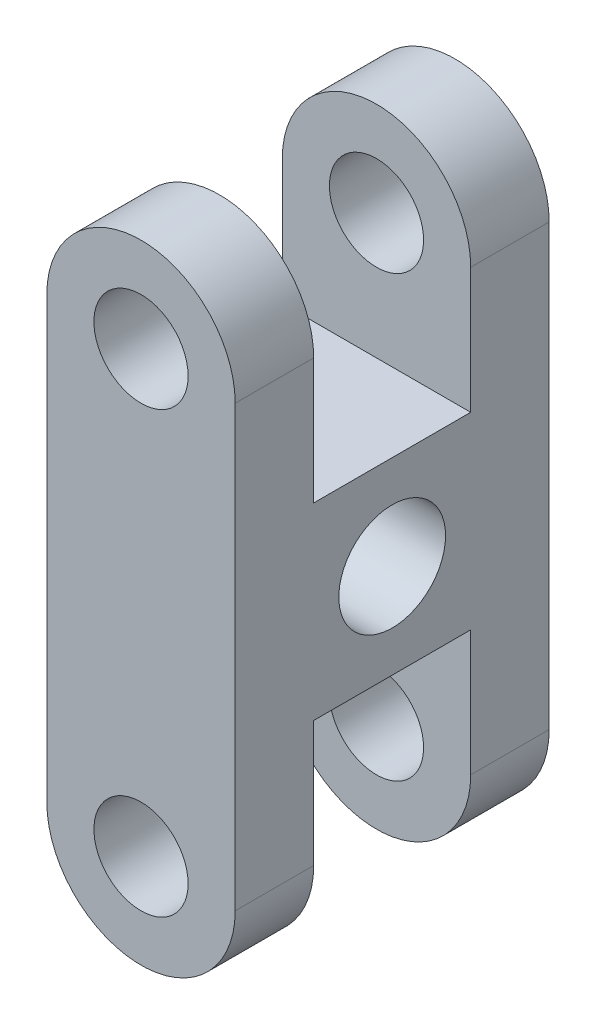
SolidWorks part; units mm, degrees
ref_plane "Plano frontal" through (0, 0, 0) normal (0, 0, 1) x (1, 0, 0)
ref_plane "Plano superior" through (0, 0, 0) normal (0, 1, 0) x (1, 0, 0)
ref_plane "Plano direito" through (0, 0, 0) normal (1, 0, 0) x (0, 0, -1)
sketch "Esboço2" plane through (0, 0, 0) normal (0, 0, 1) x (1, 0, 0)
  line L0 (0, -14) -> (0, 14) construction
  line L1 (-6, -14) -> (-6, 14)
  line L2 (6, -14) -> (6, 14)
  arc A0 (-6, -14) -> (6, -14) centre (0, -14) ccw
  arc A1 (6, 14) -> (-6, 14) centre (0, 14) ccw
  circle A2 centre (0, -14) radius 3
  circle A3 centre (0, 14) radius 3
  point P3 (0, 0)
  dimension "D1" = 6
  dimension "D2" = 6
  dimension "D3" = 28
extrude "Ressalto-extrusão1" add sketch "Esboço2" along normal blind 20
sketch "Esboço3" plane through (0, 0, 0) normal (1, 0, 0) x (0, 0, -1)
  line L0 (-15, -20) -> (-5, -20)
  line L1 (-20, -20) -> (0, -20) construction
  line L2 (0, -20) -> (0, -14) construction
  line L5 (-15, -20) -> (-15, -6)
  line L6 (-15, -6) -> (-5, -6)
  line L7 (-5, -6) -> (-5, -20)
  line L8 (0, 0) -> (-20, 0) construction
  line L9 (0, -14) -> (0, 14) construction
  line L10 (-20, -14) -> (-20, 14) construction
  line L11 (-15, 20) -> (-5, 20)
  line L12 (-15, 6) -> (-5, 6)
  line L13 (-5, 6) -> (-5, 20)
  line L14 (-15, 20) -> (-15, 6)
  circle A0 centre (-10, 0) radius 3.4
  dimension "D4" = 6.8
  dimension "D1" = 10
  dimension "D2" = 5
  dimension "D3" = 14
extrude "Corte-extrusão1" cut sketch "Esboço3" against normal through all both and the other way through all
